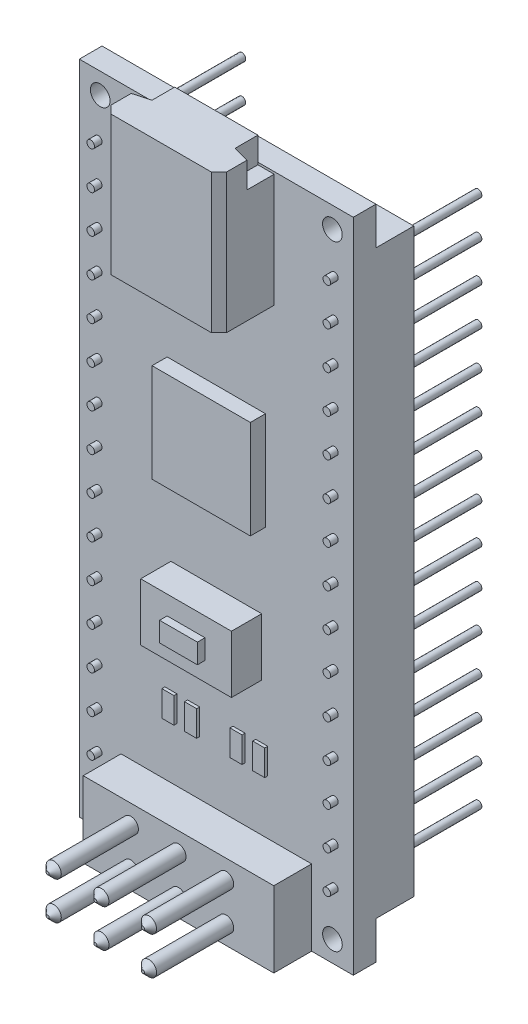
SolidWorks part; units mm, degrees
ref_plane "Plan de face" through (0, 0, 0) normal (0, 0, 1) x (1, 0, 0)
ref_plane "Plan de dessus" through (0, 0, 0) normal (0, 1, 0) x (1, 0, 0)
ref_plane "Plan de droite" through (0, 0, 0) normal (1, 0, 0) x (0, 0, -1)
sketch "Esquisse1" plane through (0, 0, 0) normal (0, 0, 1) x (1, 0, 0)
  line L1 (0, 0) -> (-18.11, 0)
  line L2 (0, 0) -> (0, 43.4)
  line L3 (0, 43.4) -> (-18.11, 43.4)
  line L4 (-18.11, 0) -> (-18.11, 43.4)
  dimension "D1" = 43.4
  dimension "D2" = 18.11
extrude "Boss.-Extru.1" add sketch "Esquisse1" along normal blind 1.5
sketch "Esquisse2" plane through (0, 0, 1.5) normal (0, 0, 1) x (1, 0, 0)
  line L0 (0, 43.4) -> (-18.11, 43.4) construction
  line L1 (-12.88, 51.05) -> (-5.23, 51.05)
  line L2 (-12.88, 51.05) -> (-12.88, 35.75)
  line L3 (-12.88, 35.75) -> (-5.23, 35.75)
  line L4 (-5.23, 51.05) -> (-5.23, 35.75)
  line L5 (-12.88, 51.05) -> (-5.23, 35.75) construction
  line L6 (-12.88, 35.75) -> (-5.23, 51.05) construction
  line L8 (-12.88, 51.05) -> (-5.23, 51.05)
  line L9 (-12.88, 51.05) -> (-12.88, 44.95)
  line L10 (-12.88, 44.95) -> (-5.23, 44.95)
  line L11 (-5.23, 51.05) -> (-5.23, 44.95)
  point P0 (-9.055, 43.4)
  line M6 (0, 43.4) -> (-18.11, 43.4)
  dimension "D1" = 7.65
  dimension "D2" = 15.3
  dimension "D3" = 9.2
extrude "Boss.-Extru.2" add sketch "Esquisse2" along normal blind 3.65 contours L4 L2 L3 M6 | L10 L2 L4 M6
sketch "Esquisse3" plane through (0, 0, 1.5) normal (0, 0, 1) x (1, 0, 0)
  line L0 (-18.11, 0) -> (0, 0) construction
  line L1 (-15.355, -5) -> (-2.755, -5)
  line L2 (-15.355, -5) -> (-15.355, 5)
  line L3 (-15.355, 5) -> (-2.755, 5)
  line L4 (-2.755, -5) -> (-2.755, 5)
  line L5 (-15.355, -5) -> (-2.755, 5) construction
  line L6 (-15.355, 5) -> (-2.755, -5) construction
  line L7 (-2.755, 0) -> (-15.355, 0)
  point P0 (-9.055, 0)
  line M11 (-18.11, 0) -> (0, 0)
  dimension "D1" = 10
  dimension "D2" = 12.6
extrude "Boss.-Extru.3" add sketch "Esquisse3" along normal blind 2.5 contours L4 L3 L2 M11
sketch "Esquisse4" plane through (0, 0, 0) normal (0, 0, -1) x (-1, 0, 0)
  line L0 (18.11, 0) -> (0, 0) construction
  line L1 (0, 43.4) -> (2.5, 43.4)
  line L2 (0, 43.4) -> (0, 0)
  line L3 (0, 0) -> (2.5, 0)
  line L4 (2.5, 43.4) -> (2.5, 0)
  line L5 (0, 43.4) -> (18.11, 43.4) construction
  line L6 (18.11, 0) -> (15.61, 0)
  line L7 (18.11, 0) -> (18.11, 43.4)
  line L8 (18.11, 43.4) -> (15.61, 43.4)
  line L9 (15.61, 0) -> (15.61, 43.4)
  line L11 (0, 43.4) -> (2.5, 43.4)
  line L12 (0, 43.4) -> (0, 40.9)
  line L13 (0, 40.9) -> (2.5, 40.9)
  line L14 (2.5, 43.4) -> (2.5, 40.9)
  line L15 (15.61, 43.4) -> (18.11, 43.4)
  line L16 (15.61, 43.4) -> (15.61, 40.9)
  line L17 (15.61, 40.9) -> (18.11, 40.9)
  line L18 (18.11, 43.4) -> (18.11, 40.9)
  line L19 (0, 0) -> (2.5, 0)
  line L20 (0, 0) -> (0, 2.5)
  line L21 (0, 2.5) -> (2.5, 2.5)
  line L22 (2.5, 0) -> (2.5, 2.5)
  line L23 (15.61, 0) -> (18.11, 0)
  line L24 (15.61, 0) -> (15.61, 2.5)
  line L25 (15.61, 2.5) -> (18.11, 2.5)
  line L26 (18.11, 0) -> (18.11, 2.5)
  dimension "D1" = 2.5
  dimension "D2" = 2.5
  dimension "D3" = 2.5
  dimension "D4" = 2.5
  dimension "D5" = 2.5
  dimension "D6" = 2.5
extrude "Boss.-Extru.4" add sketch "Esquisse4" along normal blind 2.5 contours L2 L21 L4 L13 | L9 L25 L7 L17
sketch "Esquisse5" plane through (0, 0, -2.5) normal (0, 0, -1) x (-1, 0, 0)
  line L0 (16.86, 40.9) -> (16.86, 2.5) construction
  line L1 (15.61, 40.9) -> (18.11, 40.9) construction
  line L2 (15.61, 2.5) -> (18.11, 2.5) construction
  line L3 (16.86, 40.9) -> (16.86, 39.4) construction
  line L4 (9.055, 43.4) -> (9.055, 0) construction
  line L5 (5.23, 43.4) -> (12.88, 43.4) construction
  line L6 (18.11, 0) -> (0, 0) construction
  circle A0 centre (16.86, 39.4) radius 0.25
  circle A1 centre (16.86, 36.9) radius 0.25
  circle A2 centre (16.86, 34.4) radius 0.25
  circle A3 centre (16.86, 31.9) radius 0.25
  circle A4 centre (16.86, 29.4) radius 0.25
  circle A5 centre (16.86, 26.9) radius 0.25
  circle A6 centre (16.86, 24.4) radius 0.25
  circle A7 centre (16.86, 21.9) radius 0.25
  circle A8 centre (16.86, 19.4) radius 0.25
  circle A9 centre (16.86, 16.9) radius 0.25
  circle A10 centre (16.86, 14.4) radius 0.25
  circle A11 centre (16.86, 11.9) radius 0.25
  circle A12 centre (16.86, 9.4) radius 0.25
  circle A13 centre (16.86, 6.9) radius 0.25
  circle A14 centre (16.86, 4.4) radius 0.25
  circle A15 centre (1.25, 4.4) radius 0.25
  circle A16 centre (1.25, 6.9) radius 0.25
  circle A17 centre (1.25, 9.4) radius 0.25
  circle A18 centre (1.25, 11.9) radius 0.25
  circle A19 centre (1.25, 14.4) radius 0.25
  circle A20 centre (1.25, 16.9) radius 0.25
  circle A21 centre (1.25, 19.4) radius 0.25
  circle A22 centre (1.25, 21.9) radius 0.25
  circle A23 centre (1.25, 24.4) radius 0.25
  circle A24 centre (1.25, 26.9) radius 0.25
  circle A25 centre (1.25, 29.4) radius 0.25
  circle A26 centre (1.25, 31.9) radius 0.25
  circle A27 centre (1.25, 34.4) radius 0.25
  circle A28 centre (1.25, 36.9) radius 0.25
  circle A29 centre (1.25, 39.4) radius 0.25
  dimension "D2" = 0.5
  dimension "D1" = 1.5
  dimension "D3" = 15
extrude "Boss.-Extru.5" add sketch "Esquisse5" along normal blind 5.5 and the other way blind 4.5
sketch "Esquisse6" plane through (0, 0, 1.5) normal (0, 0, 1) x (1, 0, 0)
  line L0 (-9.055, 5) -> (-9.055, 35.75) construction
  line L1 (-15.355, 5) -> (-2.755, 5) construction
  line L2 (-12.88, 35.75) -> (-5.23, 35.75) construction
  line L4 (-12.305, 29.25) -> (-5.805, 29.25)
  line L5 (-12.305, 29.25) -> (-12.305, 22.75)
  line L6 (-12.305, 22.75) -> (-5.805, 22.75)
  line L7 (-5.805, 29.25) -> (-5.805, 22.75)
  line L8 (-12.305, 29.25) -> (-5.805, 22.75) construction
  line L9 (-12.305, 22.75) -> (-5.805, 29.25) construction
  point P6 (-9.055, 26)
  dimension "D1" = 6.5
  dimension "D2" = 6.5
  dimension "D3" = 6.5
extrude "Boss.-Extru.6" add sketch "Esquisse6" along normal blind 1
sketch "Esquisse7" plane through (0, 0, 1.5) normal (0, 0, 1) x (1, 0, 0)
  line L0 (-9.055, 5) -> (-9.055, 22.75) construction
  line L1 (-15.355, 5) -> (-2.755, 5) construction
  line L2 (-12.305, 22.75) -> (-5.805, 22.75) construction
  line L4 (-6.055, 17.673) -> (-12.055, 17.673)
  line L5 (-6.055, 17.673) -> (-6.055, 13.873)
  line L6 (-6.055, 13.873) -> (-12.055, 13.873)
  line L7 (-12.055, 17.673) -> (-12.055, 13.873)
  line L8 (-6.055, 17.673) -> (-12.055, 13.873) construction
  line L9 (-6.055, 13.873) -> (-12.055, 17.673) construction
  point P6 (-9.055, 15.773)
  dimension "D1" = 3.8
  dimension "D2" = 6
extrude "Boss.-Extru.9" add sketch "Esquisse7" along normal blind 2
sketch "Esquisse8" plane through (0, 0, 3.5) normal (0, 0, 1) x (1, 0, 0)
  line L0 (-9.055, 13.873) -> (-9.055, 17.673) construction
  line L1 (-12.055, 13.873) -> (-6.055, 13.873) construction
  line L2 (-6.055, 17.673) -> (-12.055, 17.673) construction
  line L4 (-7.805, 15.123) -> (-10.305, 15.123)
  line L5 (-7.805, 15.123) -> (-7.805, 16.423)
  line L6 (-7.805, 16.423) -> (-10.305, 16.423)
  line L7 (-10.305, 15.123) -> (-10.305, 16.423)
  line L8 (-7.805, 15.123) -> (-10.305, 16.423) construction
  line L9 (-7.805, 16.423) -> (-10.305, 15.123) construction
  point P6 (-9.055, 15.773)
  dimension "D1" = 2.5
  dimension "D2" = 1.3
extrude "Boss.-Extru.10" add sketch "Esquisse8" along normal blind 0.5
sketch "Esquisse9" plane through (0, 0, 1.5) normal (0, 0, 1) x (1, 0, 0)
  line L0 (-9.055, 5) -> (-9.055, 13.873) construction
  line L1 (-15.355, 5) -> (-2.755, 5) construction
  line L2 (-12.055, 13.873) -> (-6.055, 13.873) construction
  line L3 (-9.055, 9.4365) -> (-6.055, 9.4365) construction
  line L4 (-9.055, 9.4365) -> (-12.055, 9.4365) construction
  line L6 (-6.455, 8.5865) -> (-5.655, 8.5865)
  line L7 (-6.455, 8.5865) -> (-6.455, 10.2865)
  line L8 (-6.455, 10.2865) -> (-5.655, 10.2865)
  line L9 (-5.655, 8.5865) -> (-5.655, 10.2865)
  line L10 (-6.455, 8.5865) -> (-5.655, 10.2865) construction
  line L11 (-6.455, 10.2865) -> (-5.655, 8.5865) construction
  line L12 (-10.155, 8.5865) -> (-10.955, 8.5865)
  line L13 (-10.155, 8.5865) -> (-10.155, 10.2865)
  line L14 (-10.155, 10.2865) -> (-10.955, 10.2865)
  line L15 (-10.955, 8.5865) -> (-10.955, 10.2865)
  line L16 (-10.155, 8.5865) -> (-10.955, 10.2865) construction
  line L17 (-10.155, 10.2865) -> (-10.955, 8.5865) construction
  line L18 (-7.155, 8.5865) -> (-7.955, 8.5865)
  line L19 (-7.155, 8.5865) -> (-7.155, 10.2865)
  line L20 (-7.155, 10.2865) -> (-7.955, 10.2865)
  line L21 (-7.955, 8.5865) -> (-7.955, 10.2865)
  line L22 (-7.155, 8.5865) -> (-7.955, 10.2865) construction
  line L23 (-7.155, 10.2865) -> (-7.955, 8.5865) construction
  line L24 (-12.455, 10.2865) -> (-11.655, 10.2865)
  line L25 (-12.455, 10.2865) -> (-12.455, 8.5865)
  line L26 (-12.455, 8.5865) -> (-11.655, 8.5865)
  line L27 (-11.655, 10.2865) -> (-11.655, 8.5865)
  line L28 (-12.455, 10.2865) -> (-11.655, 8.5865) construction
  line L29 (-12.455, 8.5865) -> (-11.655, 10.2865) construction
  point P8 (-10.555, 9.4365)
  point P18 (-7.555, 9.4365)
  dimension "D1" = 3
  dimension "D2" = 3
  dimension "D3" = 0.8
  dimension "D4" = 0.8
  dimension "D5" = 0.8
  dimension "D6" = 0.8
  dimension "D7" = 1.7
  dimension "D8" = 1.7
  dimension "D9" = 1.7
  dimension "D10" = 1.7
extrude "Boss.-Extru.11" add sketch "Esquisse9" along normal blind 0.2
sketch "Esquisse10" plane through (0, 0, 4) normal (0, 0, 1) x (1, 0, 0)
  line L0 (-2.755, 2.5) -> (-15.355, 2.5) construction
  line L1 (-2.755, 0) -> (-2.755, 5) construction
  line L2 (-15.355, 0) -> (-15.355, 5) construction
  line L3 (-9.055, 2.5) -> (-9.055, 5) construction
  line L4 (-15.355, 5) -> (-2.755, 5) construction
  line L5 (-9.055, 2.5) -> (-9.055, 0) construction
  line L6 (-15.355, 0) -> (-2.755, 0) construction
  line L7 (-9.055, 1.25) -> (-2.755, 1.25) construction
  line L8 (-9.055, 1.25) -> (-15.355, 1.25) construction
  line L9 (-15.355, 0) -> (-15.355, 5) construction
  line L10 (-9.055, 3.75) -> (-15.355, 3.75) construction
  line L11 (-9.055, 3.75) -> (-2.755, 3.75) construction
  circle A0 centre (-5.905, 1.25) radius 0.5
  circle A1 centre (-5.905, 3.75) radius 0.5
  circle A2 centre (-9.055, 3.75) radius 0.5
  circle A3 centre (-12.205, 3.75) radius 0.5
  circle A4 centre (-12.205, 1.25) radius 0.5
  circle A5 centre (-9.055, 1.25) radius 0.5
  dimension "D1" = 1
  dimension "D2" = 1
  dimension "D3" = 1
  dimension "D4" = 1
  dimension "D5" = 1
  dimension "D6" = 1
extrude "Boss.-Extru.12" add sketch "Esquisse10" along normal blind 5.5
chamfer "Chanfrein1" distance 0.4 angle 45 6 edges at (-11.705, 3.75, 9.5) (-11.705, 1.25, 9.5) (-8.555, 1.25, 9.5) (-8.555, 3.75, 9.5) (-5.405, 3.75, 9.5) (-5.405, 1.25, 9.5)
sketch "Esquisse11" plane through (0, 44.95, 0) normal (0, 1, 0) x (1, 0, 0)
  line L0 (-9.055, -1.5) -> (-9.055, -5.15) construction
  line L1 (-12.88, -1.5) -> (-5.23, -1.5) construction
  line L2 (-12.88, -5.15) -> (-5.23, -5.15) construction
  line L3 (-9.055, -1.5) -> (-6.305, -1.5) construction
  line L4 (-9.055, -1.5) -> (-11.805, -1.5) construction
  line L5 (-6.305, -1.5) -> (-6.305, -3)
  line L6 (-11.805, -1.5) -> (-11.805, -3)
  line L7 (-6.305, -3) -> (-5.23, -3) construction
  line L8 (-5.23, -5.15) -> (-5.23, -1.5) construction
  line L9 (-5.23, -3) -> (-5.23, -3.3) construction
  line L10 (-11.805, -3) -> (-12.88, -3) construction
  line L11 (-12.88, -5.15) -> (-12.88, -1.5) construction
  line L12 (-12.88, -3) -> (-12.88, -3.3) construction
  line L13 (-11.805, -3) -> (-12.88, -3.3)
  line L14 (-5.23, -3.3) -> (-6.305, -3)
  line L15 (-5.23, -3.3) -> (-5.23, -1.5)
  line L16 (-5.23, -1.5) -> (-6.305, -1.5)
  line L17 (-11.805, -1.5) -> (-12.88, -1.5)
  line L18 (-12.88, -1.5) -> (-12.88, -3.3)
  dimension "D1" = 2.75
  dimension "D2" = 2.75
  dimension "D3" = 1.5
  dimension "D4" = 1.5
  dimension "D5" = 0.3
  dimension "D6" = 0.3
extrude "Enlèv. mat.-Extru.1" cut sketch "Esquisse11" against normal blind 1.7
chamfer "Chanfrein2" distance 0.5 angle 45 2 edges at (-12.88, 40.35, 5.15) (-5.23, 40.35, 5.15)
sketch "Esquisse12" plane through (0, 0, 1.5) normal (0, 0, 1) x (1, 0, 0)
  line L0 (-15.355, 0) -> (-15.355, 5) construction
  line L1 (-18.11, 0) -> (-15.355, 0)
  line L2 (-18.11, 0) -> (-18.11, 2.76)
  line L3 (-18.11, 2.76) -> (-15.355, 2.76)
  line L4 (-15.355, 0) -> (-15.355, 2.76)
  line L5 (-18.11, 0) -> (-15.355, 2.76) construction
  line L6 (-2.755, 0) -> (-2.755, 5) construction
  line L7 (0, 0) -> (-2.755, 0)
  line L8 (0, 0) -> (0, 2.76)
  line L9 (0, 2.76) -> (-2.755, 2.76)
  line L10 (-2.755, 0) -> (-2.755, 2.76)
  line L11 (0, 0) -> (-2.755, 2.76) construction
  line L12 (-15.35, 40.64) -> (-18.11, 43.4) construction
  line L13 (0, 43.4) -> (-2.76, 43.4)
  line L14 (0, 43.4) -> (0, 40.64)
  line L15 (0, 40.64) -> (-2.76, 40.64)
  line L16 (-2.76, 43.4) -> (-2.76, 40.64)
  line L17 (-18.11, 43.4) -> (-15.35, 43.4)
  line L18 (-18.11, 43.4) -> (-18.11, 40.64)
  line L19 (-18.11, 40.64) -> (-15.35, 40.64)
  line L20 (-15.35, 43.4) -> (-15.35, 40.64)
  line L21 (-2.76, 40.64) -> (0, 43.4) construction
  circle A0 centre (-16.7325, 1.38) radius 0.65
  circle A1 centre (-1.3775, 1.38) radius 0.65
  circle A2 centre (-16.73, 42.02) radius 0.65
  circle A3 centre (-1.38, 42.02) radius 0.65
  dimension "D2" = 1.3
  dimension "D4" = 1.3
  dimension "D9" = 1.3
  dimension "D10" = 1.3
  dimension "D1" = 2.76
  dimension "D3" = 2.76
  dimension "D5" = 2.76
  dimension "D6" = 2.76
  dimension "D7" = 2.76
  dimension "D8" = 2.76
extrude "Enlèv. mat.-Extru.2" cut sketch "Esquisse12" against normal blind 5.7 contours A3 | A2 | A0 | A1
sketch "Esquisse13" plane through (0, 0, 0) normal (0, 0, -1) x (-1, 0, 0)
  line L0 (0, 43.4) -> (18.11, 43.4) construction
  line L1 (15.11, 6.5) -> (9.61, 6.5)
  line L2 (15.11, 6.5) -> (15.11, 9.5)
  line L3 (15.11, 9.5) -> (9.61, 9.5)
  line L4 (9.61, 6.5) -> (9.61, 9.5)
  line L5 (9, 25.4) -> (5.5, 25.4)
  line L6 (9, 25.4) -> (9, 35.4)
  line L7 (9, 35.4) -> (5.5, 35.4)
  line L8 (5.5, 25.4) -> (5.5, 35.4)
  line L9 (6.11, 39.4) -> (5.11, 39.4)
  line L10 (6.11, 39.4) -> (6.11, 42.4)
  line L11 (6.11, 42.4) -> (5.11, 42.4)
  line L12 (5.11, 39.4) -> (5.11, 42.4)
  line L13 (8.11, 42.4) -> (7.11, 42.4)
  line L14 (8.11, 42.4) -> (8.11, 39.4)
  line L15 (8.11, 39.4) -> (7.11, 39.4)
  line L16 (7.11, 42.4) -> (7.11, 39.4)
  line L17 (8.61, 6.5) -> (7.61, 6.5)
  line L18 (8.61, 6.5) -> (8.61, 9.5)
  line L19 (8.61, 9.5) -> (7.61, 9.5)
  line L20 (7.61, 6.5) -> (7.61, 9.5)
  line L21 (0, 40.9) -> (0, 2.5) construction
  line L22 (18.11, 0) -> (0, 0) construction
  line L23 (18.11, 2.5) -> (18.11, 40.9) construction
  line L24 (18.11, 43.4) -> (18.11, 40.9) construction
  line L25 (12.11, 40.4) -> (11.11, 40.4)
  line L26 (12.11, 40.4) -> (12.11, 42.4)
  line L27 (12.11, 42.4) -> (11.11, 42.4)
  line L28 (11.11, 40.4) -> (11.11, 42.4)
  line L29 (15.11, 40.4) -> (14.11, 40.4)
  line L30 (15.11, 40.4) -> (15.11, 42.4)
  line L31 (15.11, 42.4) -> (14.11, 42.4)
  line L32 (14.11, 40.4) -> (14.11, 42.4)
  line L34 (4.11, 39.4) -> (3.11, 39.4)
  line L35 (4.11, 39.4) -> (4.11, 42.4)
  line L36 (4.11, 42.4) -> (3.11, 42.4)
  line L37 (3.11, 39.4) -> (3.11, 42.4)
  dimension "D1" = 5.5
  dimension "D2" = 3
  dimension "D3" = 1
  dimension "D4" = 3
  dimension "D5" = 3.5
  dimension "D6" = 10
  dimension "D7" = 8
  dimension "D8" = 5.5
  dimension "D9" = 6.5
  dimension "D10" = 6.5
  dimension "D11" = 3
  dimension "D12" = 1
  dimension "D13" = 1
  dimension "D14" = 1
  dimension "D15" = 1
  dimension "D16" = 1
  dimension "D17" = 1
  dimension "D18" = 1
  dimension "D19" = 1
  dimension "D20" = 1
  dimension "D21" = 2
  dimension "D22" = 2
  dimension "D23" = 3
  dimension "D24" = 3
  dimension "D25" = 3
  dimension "D26" = 2
  dimension "D27" = 3
  dimension "D28" = 1
  dimension "D29" = 1
  dimension "D30" = 1
extrude "Boss.-Extru.13" add sketch "Esquisse13" along normal blind 1
